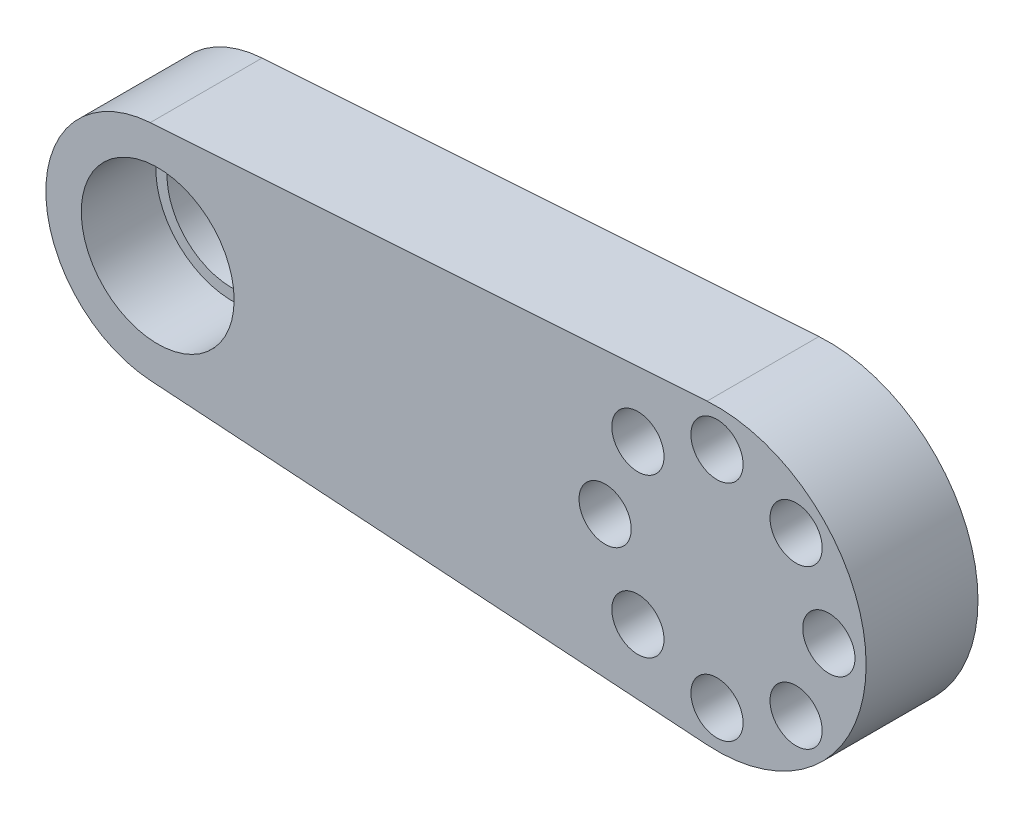
SolidWorks part; units mm, degrees
ref_plane "正面" through (0, 0, 0) normal (0, 0, 1) x (1, 0, 0)
ref_plane "平面" through (0, 0, 0) normal (0, 1, 0) x (1, 0, 0)
ref_plane "右側面" through (0, 0, 0) normal (1, 0, 0) x (0, 0, -1)
sketch "ｽｹｯﾁ1" plane through (0, 0, 0) normal (0, 0, 1) x (1, 0, 0)
  line L0 (-0.5333, 7.9822) -> (-30.4, 5.9867)
  line L1 (-0.5333, -7.9822) -> (-30.4, -5.9867)
  arc A0 (-0.5333, 7.9822) -> (-0.5333, -7.9822) centre (0, 0) cw
  arc A1 (-30.4, 5.9867) -> (-30.4, -5.9867) centre (-30, 0) ccw
  dimension "D1" = 8
  dimension "D2" = 6
  dimension "D3" = 30
extrude "ﾎﾞｽ - 押し出し1" add sketch "ｽｹｯﾁ1" along normal blind 6
sketch "ｽｹｯﾁ2" plane through (0, 0, 0) normal (0, 0, 1) x (1, 0, 0)
  circle A0 centre (0, 0) radius 6 construction
  circle A1 centre (0, 6) radius 1.4
  circle A2 centre (4.2426, 4.2426) radius 1.4
  circle A3 centre (6, 0) radius 1.4
  circle A4 centre (4.2426, -4.2426) radius 1.4
  circle A5 centre (0, -6) radius 1.4
  circle A6 centre (-4.2426, -4.2426) radius 1.4
  circle A7 centre (-6, 0) radius 1.4
  circle A8 centre (-4.2426, 4.2426) radius 1.4
  point P21 (0, 0)
  dimension "D1" = 12
  dimension "D2" = 2.8
  dimension "D3" = 8
extrude "ｶｯﾄ - 押し出し1" cut sketch "ｽｹｯﾁ2" against normal through all both and the other way through all contours A8 | A3 | A1 | A7 | A6 | A5 | A4 | A2
sketch "ｽｹｯﾁ3" plane through (0, 0, 0) normal (0, 0, -1) x (-1, 0, 0)
  circle A0 centre (0, 0) radius 4.1
  dimension "D1" = 8.2
extrude "ｶｯﾄ - 押し出し2" cut sketch "ｽｹｯﾁ3" against normal blind 1.2 contours A0
sketch "ｽｹｯﾁ4" plane through (0, 0, 6) normal (0, 0, 1) x (1, 0, 0)
  circle A0 centre (-30, 0) radius 4.1
  arc A1 (-30.4, 5.9867) -> (-30.4, -5.9867) centre (-30, 0) ccw construction
  dimension "D1" = 8.2
extrude "ｶｯﾄ - 押し出し3" cut sketch "ｽｹｯﾁ4" against normal blind 4
sketch "ｽｹｯﾁ5" plane through (0, 0, 6) normal (0, 0, 1) x (1, 0, 0)
  circle A0 centre (-30, 0) radius 3.5
  dimension "D1" = 7
extrude "ｶｯﾄ - 押し出し5" cut sketch "ｽｹｯﾁ5" against normal through all
